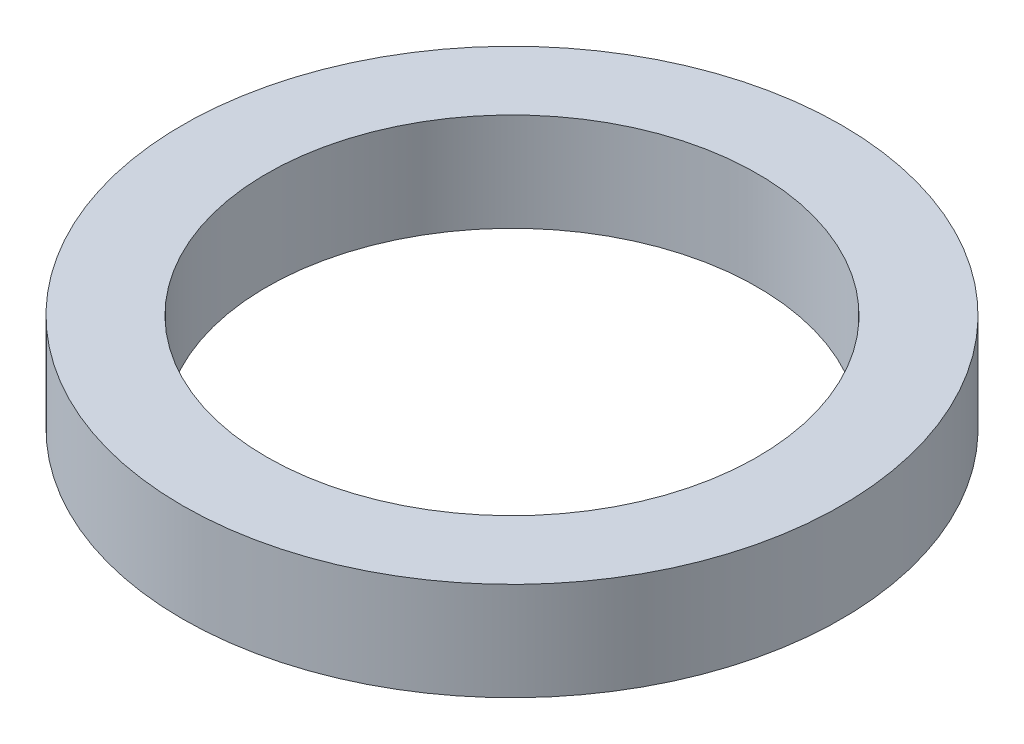
SolidWorks part; units mm, degrees
ref_plane "Спереди" through (0, 0, 0) normal (0, 0, 1) x (1, 0, 0)
ref_plane "Сверху" through (0, 0, 0) normal (0, 1, 0) x (1, 0, 0)
ref_plane "Справа" through (0, 0, 0) normal (1, 0, 0) x (0, 0, -1)
sketch "Эскиз1" plane through (0, 0, 0) normal (0, 1, 0) x (1, 0, 0)
  circle A0 centre (0, 0) radius 17.5
  circle A1 centre (0, 0) radius 23.5
  dimension "D1" = 47
  dimension "D2" = 35
extrude "тело" add sketch "Эскиз1" along normal blind 7
